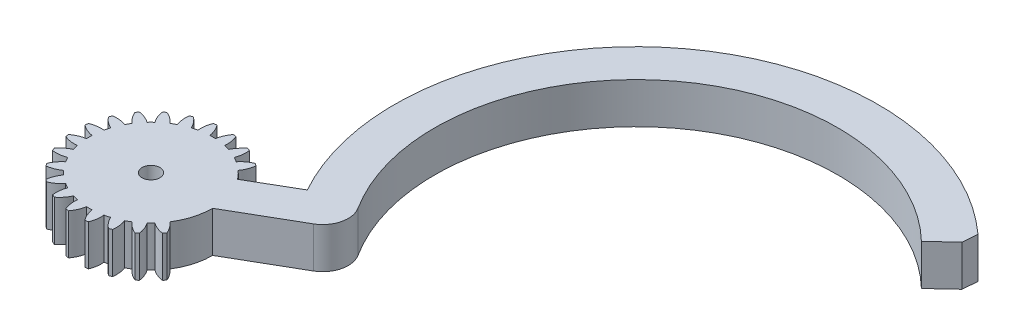
SolidWorks part; units mm, degrees
ref_plane "Alzado" through (0, 0, 0) normal (0, 0, 1) x (1, 0, 0)
ref_plane "Planta" through (0, 0, 0) normal (0, 1, 0) x (1, 0, 0)
ref_plane "Vista lateral" through (0, 0, 0) normal (1, 0, 0) x (0, 0, -1)
sketch "Croquis1" plane through (0, 0, 0) normal (0, 1, 0) x (1, 0, 0)
  line L2 (0, 0) -> (1.75, 0) construction
  line L7 (0, 0) -> (1.75, 0) construction
  line L8 (0, 0) -> (1.75, 0) construction
  line L9 (12.0927, 0) -> (97.8293, 49.5) construction
  line L10 (87.111, 63.804) -> (91.2233, 67.6388)
  line L18 (91.2233, 67.6388) -> (91.4486, 70.5448)
  line L19 (24.5971, 7.2194) -> (12.0927, 0)
  line L20 (12.0927, 0) -> (96.7359, 0) construction
  line L21 (9.6028, 7.3499) -> (18.2494, 12.3734)
  line L22 (92.9509, 69.2498) -> (110.2569, 85.3879) construction
  line L23 (29.4133, 10) -> (91.2233, 67.6388) construction
  line L24 (101.0227, 51.3437) -> (128.1865, 67.0268) construction
  arc A7 (9.6028, 7.3499) -> (8.1585, 8.926) centre (0, 0) ccw
  arc A8 (8.1585, 8.926) -> (9.1487, 11.4102) centre (3.7936, 12.1053) ccw
  arc A9 (9.1487, 11.4102) -> (8.6535, 11.7901) centre (0, 0) ccw
  arc A10 (8.6535, 11.7901) -> (6.5103, 10.1907) centre (10.711, 6.7975) ccw
  arc A11 (6.5103, 10.1907) -> (5.5703, 10.7334) centre (0, 0) ccw
  arc A12 (5.5703, 10.7334) -> (5.8838, 13.3892) centre (0.5313, 12.6747) ccw
  arc A13 (5.8838, 13.3892) -> (5.3071, 13.6281) centre (0, 0) ccw
  arc A14 (5.3071, 13.6281) -> (3.6509, 11.5285) centre (10.1523, 8.1031) ccw
  arc A15 (3.6509, 11.5285) -> (2.6025, 11.8094) centre (0, 0) ccw
  arc A16 (2.6025, 11.8094) -> (2.2179, 14.4558) centre (-2.7673, 12.3803) ccw
  arc A17 (2.2179, 14.4558) -> (1.5991, 14.5373) centre (0, 0) ccw
  arc A18 (1.5991, 14.5373) -> (0.5427, 12.0806) centre (5.8773, 11.2423) ccw
  arc A19 (0.5427, 12.0806) -> (-0.5427, 12.0806) centre (0, 0) ccw
  arc A20 (-0.5427, 12.0806) -> (-1.5991, 14.5373) centre (-5.8773, 11.2423) ccw
  arc A21 (-1.5991, 14.5373) -> (-2.2179, 14.4558) centre (0, 0) ccw
  arc A22 (-2.2179, 14.4558) -> (-2.6025, 11.8094) centre (2.7673, 12.3803) ccw
  arc A23 (-2.6025, 11.8094) -> (-3.6509, 11.5285) centre (0, 0) ccw
  arc A24 (-3.6509, 11.5285) -> (-5.3071, 13.6281) centre (-8.5867, 9.3381) ccw
  arc A25 (-5.3071, 13.6281) -> (-5.8838, 13.3892) centre (0, 0) ccw
  arc A26 (-5.8838, 13.3892) -> (-5.5703, 10.7334) centre (-0.5313, 12.6747) ccw
  arc A27 (-5.5703, 10.7334) -> (-6.5103, 10.1907) centre (0, 0) ccw
  arc A28 (-6.5103, 10.1907) -> (-8.6535, 11.7901) centre (-10.711, 6.7975) ccw
  arc A29 (-8.6535, 11.7901) -> (-9.1487, 11.4102) centre (0, 0) ccw
  arc A30 (-9.1487, 11.4102) -> (-8.1585, 8.926) centre (-3.7936, 12.1053) ccw
  arc A31 (-8.1585, 8.926) -> (-8.926, 8.1585) centre (0, 0) ccw
  arc A32 (-8.926, 8.1585) -> (-11.4102, 9.1487) centre (-12.1053, 3.7936) ccw
  arc A33 (-11.4102, 9.1487) -> (-11.7901, 8.6535) centre (0, 0) ccw
  arc A34 (-11.7901, 8.6535) -> (-10.1907, 6.5103) centre (-6.7975, 10.711) ccw
  arc A35 (-10.1907, 6.5103) -> (-10.7334, 5.5703) centre (0, 0) ccw
  arc A36 (-10.7334, 5.5703) -> (-13.3892, 5.8838) centre (-12.6747, 0.5313) ccw
  arc A37 (-13.3892, 5.8838) -> (-13.6281, 5.3071) centre (0, 0) ccw
  arc A38 (-13.6281, 5.3071) -> (-11.5285, 3.6509) centre (-9.3381, 8.5867) ccw
  arc A39 (-11.5285, 3.6509) -> (-11.8094, 2.6025) centre (0, 0) ccw
  arc A40 (-11.8094, 2.6025) -> (-14.4558, 2.2179) centre (-12.3803, -2.7673) ccw
  arc A41 (-14.4558, 2.2179) -> (-14.5373, 1.5991) centre (0, 0) ccw
  arc A42 (-14.5373, 1.5991) -> (-12.0806, 0.5427) centre (-11.2423, 5.8773) ccw
  arc A43 (-12.0806, 0.5427) -> (-12.0806, -0.5427) centre (0, 0) ccw
  arc A44 (-12.0806, -0.5427) -> (-14.5373, -1.5991) centre (-11.2423, -5.8773) ccw
  arc A45 (-14.5373, -1.5991) -> (-14.4558, -2.2179) centre (0, 0) ccw
  arc A46 (-14.4558, -2.2179) -> (-11.8094, -2.6025) centre (-12.3803, 2.7673) ccw
  arc A47 (-11.8094, -2.6025) -> (-11.5285, -3.6509) centre (0, 0) ccw
  arc A48 (-11.5285, -3.6509) -> (-13.6281, -5.3071) centre (-9.3381, -8.5867) ccw
  arc A49 (-13.6281, -5.3071) -> (-13.3892, -5.8838) centre (0, 0) ccw
  arc A50 (-13.3892, -5.8838) -> (-10.7334, -5.5703) centre (-12.6747, -0.5313) ccw
  arc A51 (-10.7334, -5.5703) -> (-10.1907, -6.5103) centre (0, 0) ccw
  arc A52 (-10.1907, -6.5103) -> (-11.7901, -8.6535) centre (-6.7975, -10.711) ccw
  arc A53 (-11.7901, -8.6535) -> (-11.4102, -9.1487) centre (0, 0) ccw
  arc A54 (-11.4102, -9.1487) -> (-8.926, -8.1585) centre (-12.1053, -3.7936) ccw
  arc A55 (-8.926, -8.1585) -> (-8.1585, -8.926) centre (0, 0) ccw
  arc A56 (-8.1585, -8.926) -> (-9.1487, -11.4102) centre (-3.7936, -12.1053) ccw
  arc A57 (-9.1487, -11.4102) -> (-8.6535, -11.7901) centre (0, 0) ccw
  arc A58 (-8.6535, -11.7901) -> (-6.5103, -10.1907) centre (-10.711, -6.7975) ccw
  arc A59 (-6.5103, -10.1907) -> (-5.5703, -10.7334) centre (0, 0) ccw
  arc A60 (-5.5703, -10.7334) -> (-5.8838, -13.3892) centre (-0.5313, -12.6747) ccw
  arc A61 (-5.8838, -13.3892) -> (-5.3071, -13.6281) centre (0, 0) ccw
  arc A62 (-5.3071, -13.6281) -> (-3.6509, -11.5285) centre (-8.5867, -9.3381) ccw
  arc A63 (-3.6509, -11.5285) -> (-2.6025, -11.8094) centre (0, 0) ccw
  arc A64 (-2.6025, -11.8094) -> (-2.2179, -14.4558) centre (2.7673, -12.3803) ccw
  arc A65 (-2.2179, -14.4558) -> (-1.5991, -14.5373) centre (0, 0) ccw
  arc A66 (-1.5991, -14.5373) -> (-0.5427, -12.0806) centre (-5.8773, -11.2423) ccw
  arc A67 (-0.5427, -12.0806) -> (0.5427, -12.0806) centre (0, 0) ccw
  arc A68 (0.5427, -12.0806) -> (1.5991, -14.5373) centre (5.8773, -11.2423) ccw
  arc A69 (1.5991, -14.5373) -> (2.2179, -14.4558) centre (0, 0) ccw
  arc A70 (2.2179, -14.4558) -> (2.6025, -11.8094) centre (-2.7673, -12.3803) ccw
  arc A71 (2.6025, -11.8094) -> (3.6509, -11.5285) centre (0, 0) ccw
  arc A72 (3.6509, -11.5285) -> (5.3071, -13.6281) centre (8.5867, -9.3381) ccw
  arc A73 (5.3071, -13.6281) -> (5.8838, -13.3892) centre (0, 0) ccw
  arc A74 (5.8838, -13.3892) -> (5.5703, -10.7334) centre (0.5313, -12.6747) ccw
  arc A75 (5.5703, -10.7334) -> (6.5103, -10.1907) centre (0, 0) ccw
  arc A76 (6.5103, -10.1907) -> (8.6535, -11.7901) centre (10.711, -6.7975) ccw
  arc A77 (8.6535, -11.7901) -> (9.1487, -11.4102) centre (0, 0) ccw
  arc A78 (9.1487, -11.4102) -> (8.1585, -8.926) centre (3.7936, -12.1053) ccw
  arc A79 (8.1585, -8.926) -> (8.926, -8.1585) centre (0, 0) ccw
  arc A80 (8.926, -8.1585) -> (11.4102, -9.1487) centre (12.1053, -3.7936) ccw
  arc A81 (11.4102, -9.1487) -> (11.7901, -8.6535) centre (0, 0) ccw
  arc A82 (11.7901, -8.6535) -> (10.1907, -6.5103) centre (6.7975, -10.711) ccw
  arc A83 (10.1907, -6.5103) -> (10.7334, -5.5703) centre (0, 0) ccw
  circle A88 centre (0, 0) radius 1.75
  arc A98 (-10.1907, 6.5103) -> (-10.7334, 5.5703) centre (0, 0) ccw construction
  arc A102 (-10.1907, 6.5103) -> (-10.7334, 5.5703) centre (0, 0) ccw
  arc A103 (-8.1585, 8.926) -> (-8.926, 8.1585) centre (0, 0) ccw
  arc A104 (-8.1585, 8.926) -> (-8.926, 8.1585) centre (0, 0) ccw construction
  arc A105 (-5.5703, 10.7334) -> (-6.5103, 10.1907) centre (0, 0) ccw
  arc A106 (-5.5703, 10.7334) -> (-6.5103, 10.1907) centre (0, 0) ccw construction
  arc A107 (-2.6025, 11.8094) -> (-3.6509, 11.5285) centre (0, 0) ccw
  arc A108 (-2.6025, 11.8094) -> (-3.6509, 11.5285) centre (0, 0) ccw construction
  arc A109 (0.5427, 12.0806) -> (-0.5427, 12.0806) centre (0, 0) ccw
  arc A110 (0.5427, 12.0806) -> (-0.5427, 12.0806) centre (0, 0) ccw construction
  arc A111 (3.6509, 11.5285) -> (2.6025, 11.8094) centre (0, 0) ccw
  arc A112 (3.6509, 11.5285) -> (2.6025, 11.8094) centre (0, 0) ccw construction
  arc A113 (6.5103, 10.1907) -> (5.5703, 10.7334) centre (0, 0) ccw
  arc A114 (6.5103, 10.1907) -> (5.5703, 10.7334) centre (0, 0) ccw construction
  arc A115 (9.6028, 7.3499) -> (8.1585, 8.926) centre (0, 0) ccw
  arc A116 (9.6028, 7.3499) -> (8.1585, 8.926) centre (0, 0) ccw construction
  arc A117 (10.1907, -6.5103) -> (12.0927, 0) centre (0, 0) ccw
  arc A118 (10.1907, -6.5103) -> (12.0927, 0) centre (0, 0) ccw construction
  arc A119 (8.1585, -8.926) -> (8.926, -8.1585) centre (0, 0) ccw
  arc A120 (8.1585, -8.926) -> (8.926, -8.1585) centre (0, 0) ccw construction
  arc A121 (5.5703, -10.7334) -> (6.5103, -10.1907) centre (0, 0) ccw
  arc A122 (5.5703, -10.7334) -> (6.5103, -10.1907) centre (0, 0) ccw construction
  arc A123 (2.6025, -11.8094) -> (3.6509, -11.5285) centre (0, 0) ccw
  arc A124 (2.6025, -11.8094) -> (3.6509, -11.5285) centre (0, 0) ccw construction
  arc A125 (-0.5427, -12.0806) -> (0.5427, -12.0806) centre (0, 0) ccw
  arc A126 (-0.5427, -12.0806) -> (0.5427, -12.0806) centre (0, 0) ccw construction
  arc A127 (-3.6509, -11.5285) -> (-2.6025, -11.8094) centre (0, 0) ccw
  arc A128 (-3.6509, -11.5285) -> (-2.6025, -11.8094) centre (0, 0) ccw construction
  arc A129 (-6.5103, -10.1907) -> (-5.5703, -10.7334) centre (0, 0) ccw
  arc A130 (-6.5103, -10.1907) -> (-5.5703, -10.7334) centre (0, 0) ccw construction
  arc A131 (-8.926, -8.1585) -> (-8.1585, -8.926) centre (0, 0) ccw
  arc A132 (-8.926, -8.1585) -> (-8.1585, -8.926) centre (0, 0) ccw construction
  arc A133 (-10.7334, -5.5703) -> (-10.1907, -6.5103) centre (0, 0) ccw
  arc A134 (-10.7334, -5.5703) -> (-10.1907, -6.5103) centre (0, 0) ccw construction
  arc A135 (-11.8094, -2.6025) -> (-11.5285, -3.6509) centre (0, 0) ccw
  arc A136 (-11.8094, -2.6025) -> (-11.5285, -3.6509) centre (0, 0) ccw construction
  arc A137 (-12.0806, 0.5427) -> (-12.0806, -0.5427) centre (0, 0) ccw construction
  arc A138 (-12.0806, 0.5427) -> (-12.0806, -0.5427) centre (0, 0) ccw
  arc A139 (-11.5285, 3.6509) -> (-11.8094, 2.6025) centre (0, 0) ccw construction
  arc A140 (-11.5285, 3.6509) -> (-11.8094, 2.6025) centre (0, 0) ccw
  arc A141 (26.319, 14.2282) -> (87.111, 63.804) centre (59.672, 35.3901) cw
  arc A142 (91.4486, 70.5448) -> (18.2494, 12.3734) centre (59.672, 35.3901) ccw
  arc A143 (24.5971, 7.2194) -> (26.319, 14.2282) centre (22.0971, 11.5495) ccw
  dimension "D1" = 20
  dimension "D2" = 10
  dimension "D3" = 13
  dimension "D4" = 39.5
  dimension "D5" = 5
extrude "Saliente-Extruir1" add sketch "Croquis1" along normal blind 8
